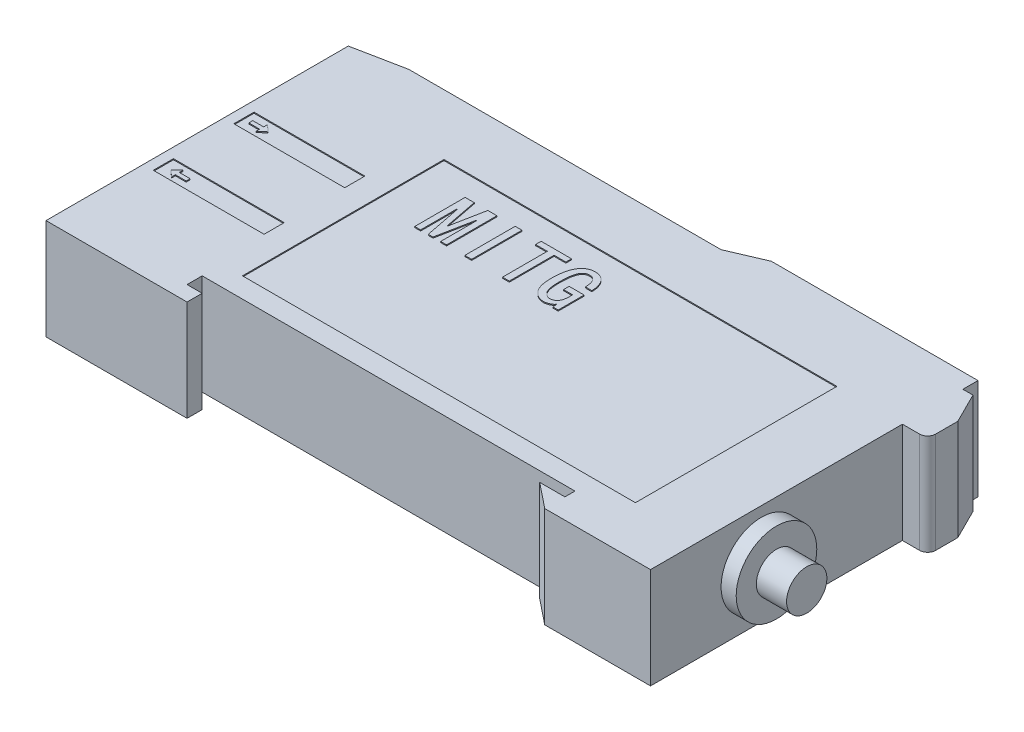
SolidWorks part; units mm, degrees
ref_plane "前视基准面" through (0, 0, 0) normal (0, 0, 1) x (1, 0, 0)
ref_plane "上视基准面" through (0, 0, 0) normal (0, 1, 0) x (1, 0, 0)
ref_plane "右视基准面" through (0, 0, 0) normal (1, 0, 0) x (0, 0, -1)
sketch "草图1" plane through (0, 0, 0) normal (0, 1, 0) x (1, 0, 0)
  line L1 (0, 0) -> (60, 0)
  line L2 (0, 0) -> (0, 31)
  line L3 (0, 31) -> (60, 31)
  line L4 (60, 0) -> (60, 31)
  dimension "D1" = 60
  dimension "D2" = 31
extrude "凸台-拉伸1" add sketch "草图1" along normal blind 10
sketch "草图2" plane through (0, 10, 0) normal (0, 1, 0) x (1, 0, 0)
  line L0 (14, 0) -> (14, 1.5)
  line L1 (0, 0) -> (60, 0) construction
  line L2 (14, 1.5) -> (12.5, 1.5)
  line L3 (12.5, 1.5) -> (12.5, 3)
  line L4 (12.5, 3) -> (49.5, 3)
  line L5 (49.5, 3) -> (49.5, 2)
  line L6 (49.5, 2) -> (47, 2)
  line L7 (47, 2) -> (49.5, 0)
  line L8 (49.5, 0) -> (14, 0)
  line L9 (0, 31) -> (0, 0) construction
  line L10 (60, 0) -> (60, 31) construction
  line L11 (0, 30) -> (5, 31)
  line L12 (60, 31) -> (0, 31) construction
  line L13 (5, 31) -> (0, 31)
  line L14 (0, 31) -> (0, 30)
  dimension "D1" = 3
  dimension "D2" = 1.5
  dimension "D3" = 14
  dimension "D4" = 12.5
  dimension "D5" = 13
  dimension "D6" = 10.5
  dimension "D7" = 10.5
  dimension "D8" = 2
  dimension "D9" = 5
  dimension "D10" = 1
extrude "切除-拉伸1" cut sketch "草图2" against normal blind 10
sketch "草图3" plane through (0, 10, 0) normal (0, 1, 0) x (1, 0, 0)
  line L0 (60, 31) -> (61, 31)
  line L1 (60, 0) -> (60, 31) construction
  line L2 (61, 31) -> (62.5, 28)
  line L3 (62.5, 28) -> (62.5, 25.8)
  line L4 (61.7, 25) -> (60, 25)
  line L6 (60, 25) -> (60, 31)
  line L7 (60, 31) -> (60, 32.5)
  line L8 (60, 32.5) -> (39.5, 32.5)
  line L9 (39.5, 32.5) -> (36, 31)
  line L10 (60, 31) -> (5, 31) construction
  line L11 (36, 31) -> (60, 31)
  arc A0 (62.5, 25.8) -> (61.7, 25) centre (61.7, 25.8) cw
  point P9 (60.85, 25)
  point P18 (62.5, 25)
  dimension "D8" = 0.8
  dimension "D1" = 1.5
  dimension "D2" = 20.5
  dimension "D3" = 24
  dimension "D4" = 6
  dimension "D5" = 2.5
  dimension "D6" = 1
  dimension "D7" = 3
extrude "凸台-拉伸2" add sketch "草图3" against normal through all
sketch "草图4" plane through (0, 0, 0) normal (-1, 0, 0) x (0, 0, 1)
  line L0 (0, 10) -> (0, 0) construction
  line L1 (-31, 10) -> (-31, 0) construction
  circle A0 centre (-18.5, 5) radius 1
  circle A1 centre (-10.5, 5) radius 1
  point P8 (-31, 5)
  dimension "D3" = 2
  dimension "D1" = 10.5
  dimension "D2" = 8
extrude "切除-拉伸2" cut sketch "草图4" against normal blind 10
sketch "草图5" plane through (0, 10, 0) normal (0, 1, 0) x (1, 0, 0)
  line L0 (0, 0) -> (14, 0) construction
  line L1 (14.5, 25) -> (53.5, 25)
  line L2 (14.5, 25) -> (14.5, 5)
  line L3 (14.5, 5) -> (53.5, 5)
  line L4 (53.5, 25) -> (53.5, 5)
  line L5 (1, 19.6468) -> (12, 19.6468)
  line L6 (1, 19.6468) -> (1, 17.6468)
  line L7 (1, 17.6468) -> (12, 17.6468)
  line L8 (12, 19.6468) -> (12, 17.6468)
  line L9 (1, 11.6468) -> (12, 11.6468)
  line L10 (1, 11.6468) -> (1, 9.6468)
  line L11 (1, 9.6468) -> (12, 9.6468)
  line L12 (12, 11.6468) -> (12, 9.6468)
  line L13 (0, 30) -> (0, 0) construction
  line L26 (49.5, 3) -> (12.5, 3) construction
  text T0 "<b>→</b>" font "华文琥珀" height 2
  text T1 "<b>←</b>" font "华文琥珀" height 2
  text T2 "MITG" font "黑体" height 5
  point P12 (1, 10.6468)
  dimension "D1" = 11
  dimension "D2" = 2
  dimension "D3" = 10.6468
  dimension "D4" = 8
  dimension "D5" = 1
  dimension "D6" = 39
  dimension "D7" = 20
  dimension "D8" = 2.5
  dimension "D9" = 2
extrude "切除-拉伸3" cut sketch "草图5" against normal blind 0.1
sketch "草图6" plane through (60, 0, 0) normal (1, 0, 0) x (0, 0, -1)
  line L0 (0, 10) -> (0, 0) construction
  circle A0 centre (11, 5) radius 4
  point P4 (0, 5)
  dimension "D1" = 8
  dimension "D2" = 11
extrude "凸台-拉伸3" add sketch "草图6" along normal blind 1.5
sketch "草图7" plane through (61.5, 0, 0) normal (1, 0, 0) x (0, 0, -1)
  circle A0 centre (11, 5) radius 2
  dimension "D1" = 4
extrude "凸台-拉伸4" add sketch "草图7" along normal blind 3
